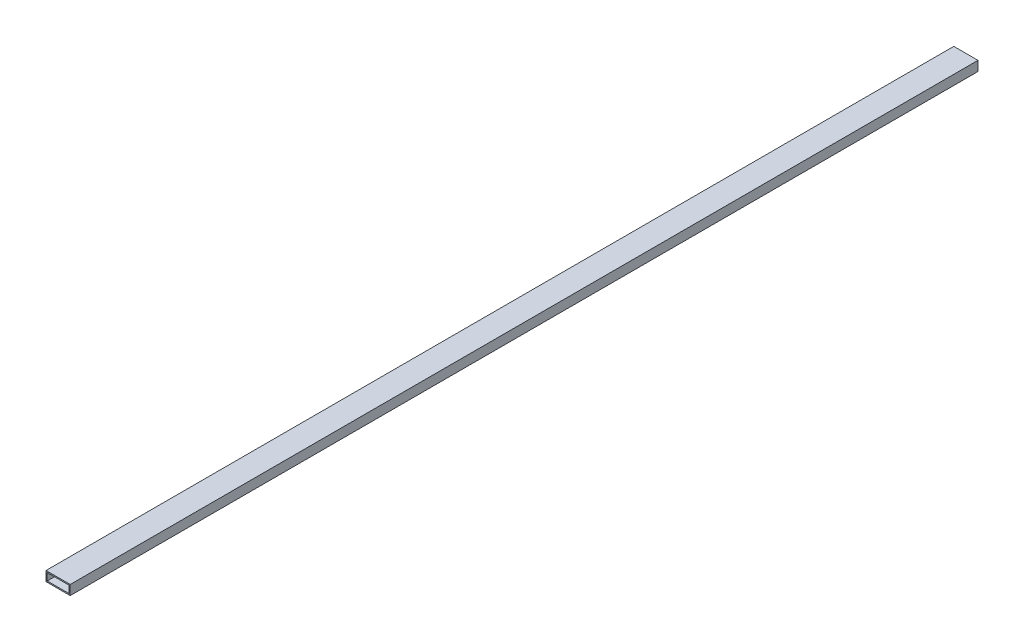
SolidWorks part; units mm, degrees
ref_plane "前视基准面" through (0, 0, 0) normal (0, 0, 1) x (1, 0, 0)
ref_plane "上视基准面" through (0, 0, 0) normal (0, 1, 0) x (1, 0, 0)
ref_plane "右视基准面" through (0, 0, 0) normal (1, 0, 0) x (0, 0, -1)
sketch "草图1" plane through (0, 0, 0) normal (0, 0, 1) x (1, 0, 0)
  line L0 (-9, 3) -> (9, 3)
  line L1 (-10, 4) -> (10, 4)
  line L2 (-10, 4) -> (-10, -4)
  line L3 (-10, -4) -> (10, -4)
  line L4 (10, 4) -> (10, -4)
  line L5 (9, 3) -> (9, -3)
  line L6 (-9, -3) -> (9, -3)
  line L7 (-9, 3) -> (-9, -3)
  point P4 (0, 4)
  point P6 (10, 0)
  dimension "D1" = 8
  dimension "D2" = 20
  dimension "D3" = 1
extrude "凸台-拉伸1" add sketch "草图1" along normal mid plane 750
